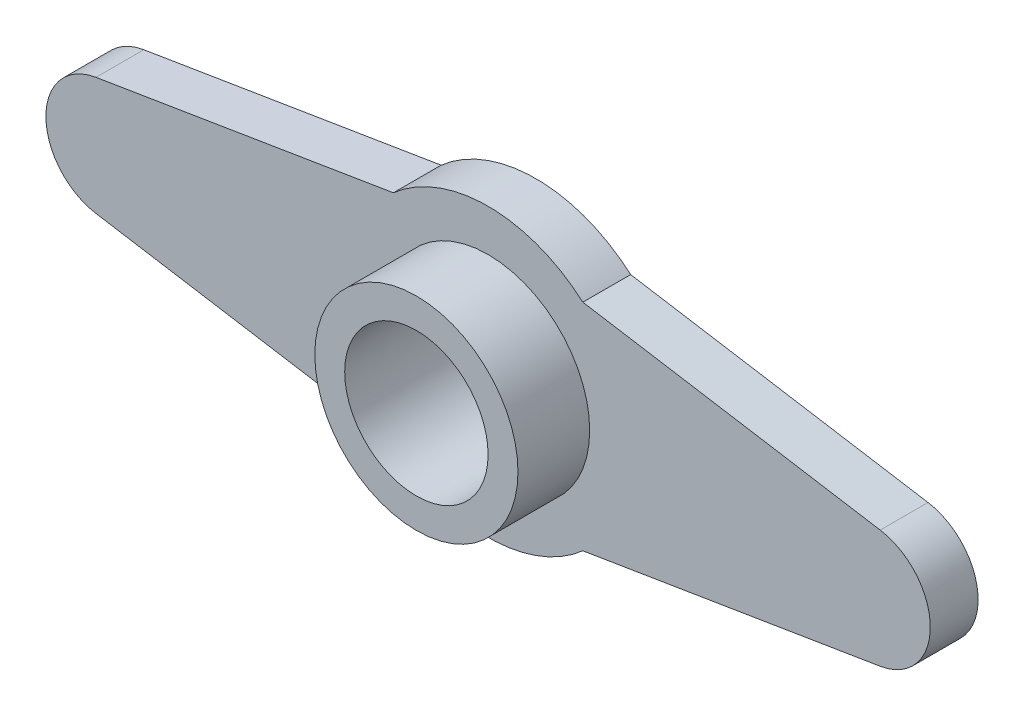
SolidWorks part; units mm, degrees
ref_plane "Front Plane" through (0, 0, 0) normal (0, 0, 1) x (1, 0, 0)
ref_plane "Top Plane" through (0, 0, 0) normal (0, 1, 0) x (1, 0, 0)
ref_plane "Right Plane" through (0, 0, 0) normal (1, 0, 0) x (0, 0, -1)
sketch "Sketch1" plane through (0, 0, 0) normal (0, 0, 1) x (1, 0, 0)
  line L0 (-3.9638, 4.5043) -> (-16.404, 2.4671)
  line L7 (-3.9638, -4.5043) -> (-16.404, -2.4671)
  line L8 (3.9638, 4.5043) -> (16.404, 2.4671)
  line L9 (3.9638, -4.5043) -> (16.404, -2.4671)
  arc A0 (-3.9638, -4.5043) -> (3.9638, -4.5043) centre (0, 0) ccw
  arc A1 (16.404, -2.4671) -> (16.404, 2.4671) centre (16, 0) ccw
  arc A2 (-16.404, 2.4671) -> (-16.404, -2.4671) centre (-16, 0) ccw
  arc A3 (3.9638, 4.5043) -> (-3.9638, 4.5043) centre (0, 0) ccw
  point P3 (16, 0)
  point P4 (-16, 0)
  dimension "D1" = 12
  dimension "D4" = 5
  dimension "D5" = 5
  dimension "D2" = 16
  dimension "D3" = 16
  dimension "D6" = 9.0086
  dimension "D7" = 7.9275
extrude "Boss-Extrude1" add sketch "Sketch1" along normal blind 2
sketch "Sketch2" plane through (0, 0, 2) normal (0, 0, 1) x (1, 0, 0)
  circle A0 centre (0, 0) radius 4.25
  dimension "D1" = 8.5
extrude "Boss-Extrude2" add sketch "Sketch2" along normal blind 3
sketch "Sketch3" plane through (0, 0, 0) normal (0, 0, -1) x (-1, 0, 0)
  circle A0 centre (0, 0) radius 3
  dimension "D1" = 6
extrude "Cut-Extrude1" cut sketch "Sketch3" against normal up to next
